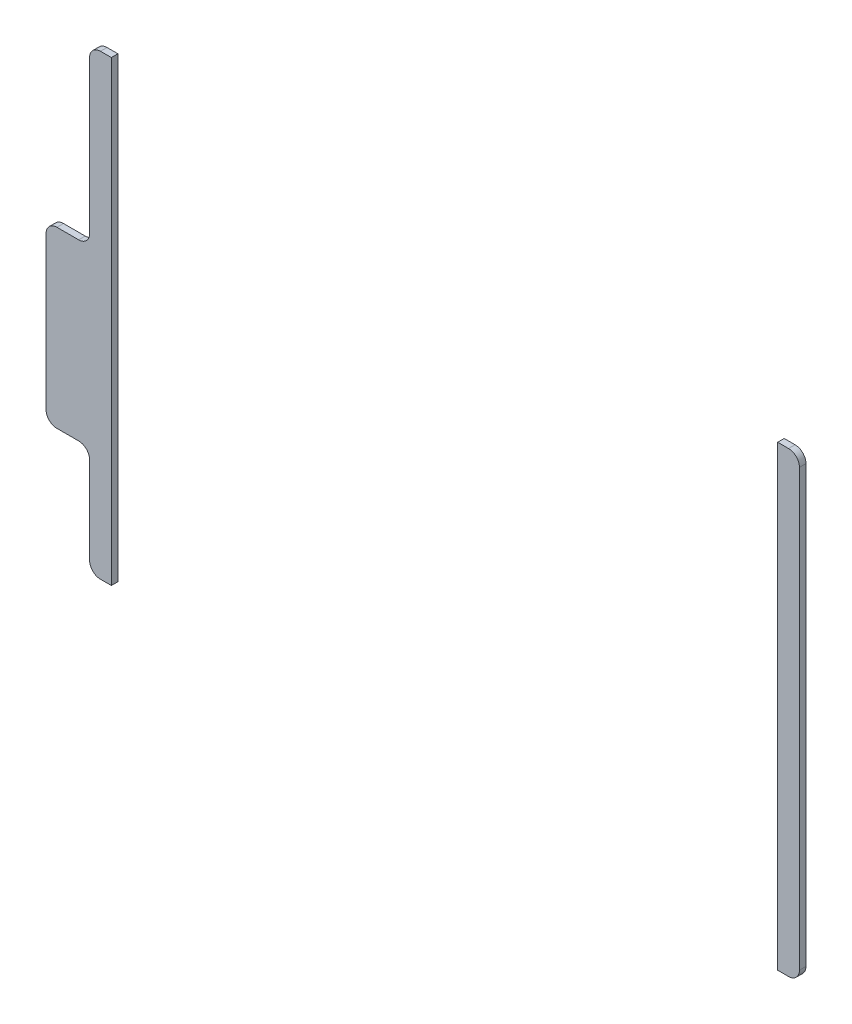
SolidWorks part; units mm, degrees
ref_plane "Спереди" through (0, 0, 0) normal (0, 0, 1) x (1, 0, 0)
ref_plane "Сверху" through (0, 0, 0) normal (0, 1, 0) x (1, 0, 0)
ref_plane "Справа" through (0, 0, 0) normal (1, 0, 0) x (0, 0, -1)
sketch "Эскиз1" plane through (0, 0, 0) normal (0, 0, 1) x (1, 0, 0)
  line L0 (-30.6, -21) -> (-31.6, -21)
  line L1 (-30.6, 21) -> (30.6, 21) construction
  line L2 (-30.6, 21) -> (-30.6, -21) construction
  line L3 (-30.6, -21) -> (30.6, -21) construction
  line L4 (30.6, 21) -> (30.6, -21) construction
  line L5 (-30.6, 21) -> (30.6, -21) construction
  line L6 (-30.6, -21) -> (30.6, 21) construction
  line L8 (-30.6, 21) -> (-30.6, -21)
  line L11 (30.6, 21) -> (31.6, 21)
  line L12 (30.6, 21) -> (30.6, -21)
  line L13 (30.6, -21) -> (31.6, -21)
  line L14 (32.6, 20) -> (32.6, -20)
  line L15 (-30.6, 21) -> (-31.6, 21)
  line L16 (-32.6, -20) -> (-32.6, -12)
  line L17 (-33.6, -11) -> (-35.6, -11)
  line L18 (-36.6, -10) -> (-36.6, 4)
  line L19 (-35.6, 5) -> (-33.6, 5)
  line L20 (-32.6, 6) -> (-32.6, 20)
  arc A0 (-31.6, 21) -> (-32.6, 20) centre (-31.6, 20) ccw
  arc A1 (-33.6, 5) -> (-32.6, 6) centre (-33.6, 6) ccw
  arc A2 (-32.6, -12) -> (-33.6, -11) centre (-33.6, -12) ccw
  arc A3 (-31.6, -21) -> (-32.6, -20) centre (-31.6, -20) cw
  arc A4 (31.6, -21) -> (32.6, -20) centre (31.6, -20) ccw
  arc A5 (31.6, 21) -> (32.6, 20) centre (31.6, 20) cw
  arc A6 (-35.6, -11) -> (-36.6, -10) centre (-35.6, -10) cw
  arc A7 (-36.6, 4) -> (-35.6, 5) centre (-35.6, 4) cw
  point P0 (0, 0)
  point P16 (-32.6, 21)
  point P19 (-32.6, 5)
  point P24 (-32.6, -21)
  point P27 (32.6, -21)
  point P32 (-36.6, -11)
  point P35 (-36.6, 5)
  dimension "D8" = 1
  dimension "D9" = 1
  dimension "D1" = 61.2
  dimension "D2" = 42
  dimension "D3" = 2
  dimension "D4" = 2
  dimension "D5" = 16
  dimension "D6" = 16
  dimension "D7" = 6
extrude "Бобышка-Вытянуть1" add sketch "Эскиз1" along normal blind 0.6
